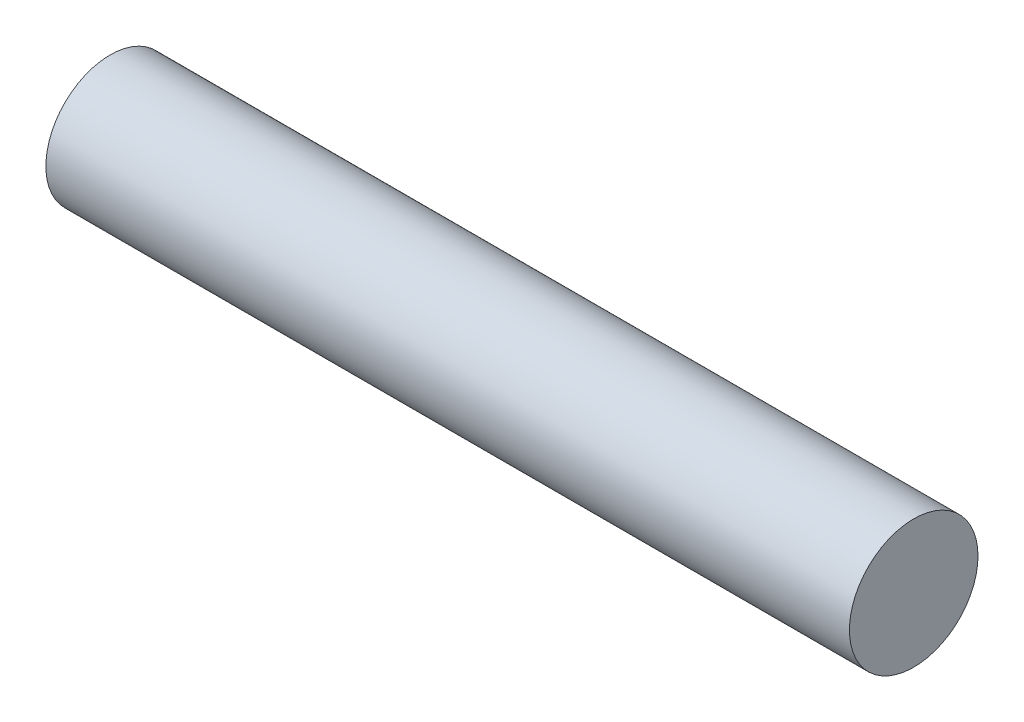
SolidWorks part; units mm, degrees
ref_plane "Front Plane" through (0, 0, 0) normal (0, 0, 1) x (1, 0, 0)
ref_plane "Top Plane" through (0, 0, 0) normal (0, 1, 0) x (1, 0, 0)
ref_plane "Right Plane" through (0, 0, 0) normal (1, 0, 0) x (0, 0, -1)
sketch "Sketch1" plane through (0, 0, 0) normal (1, 0, 0) x (0, 0, -1)
  circle A0 centre (0, 0) radius 80
extrude "FoamBody" add sketch "Sketch1" against normal blind 1000 separate body
sketch "Sketch2" plane through (0, 0, 0) normal (0, 1, 0) x (1, 0, 0)
  line L1 (-427.5, -30) -> (-262.5, -30)
  line L2 (-427.5, -30) -> (-427.5, 30)
  line L3 (-427.5, 30) -> (-262.5, 30)
  line L4 (-262.5, -30) -> (-262.5, 30)
extrude "battery bay" cut sketch "Sketch2" against normal blind 60 from offset 10
sketch "Sketch3" plane through (0, 0, 0) normal (0, 1, 0) x (1, 0, 0)
  line L1 (-300, -40) -> (-150, -40)
  line L2 (-300, -40) -> (-300, 40)
  line L3 (-300, 40) -> (-150, 40)
  line L4 (-150, -40) -> (-150, 40)
extrude "Foam" cut sketch "Sketch3" along normal blind 35 from offset 10
sketch "Sketch4" plane through (0, 0, 0) normal (0, 1, 0) x (1, 0, 0)
  line L1 (-422.5, -24) -> (-267.5, -24)
  line L2 (-422.5, -24) -> (-422.5, 24)
  line L3 (-422.5, 24) -> (-267.5, 24)
  line L4 (-267.5, -24) -> (-267.5, 24)
extrude "Battery" add sketch "Sketch4" along normal blind 3 and the other way blind 47 separate body
sketch "Sketch5" plane through (0, 0, 0) normal (0, 1, 0) x (1, 0, 0)
  line L1 (-251, -16) -> (-199, -16)
  line L2 (-251, -16) -> (-251, 16)
  line L3 (-251, 16) -> (-199, 16)
  line L4 (-199, -16) -> (-199, 16)
extrude "FC" add sketch "Sketch5" along normal blind 17 from offset 13 separate body
